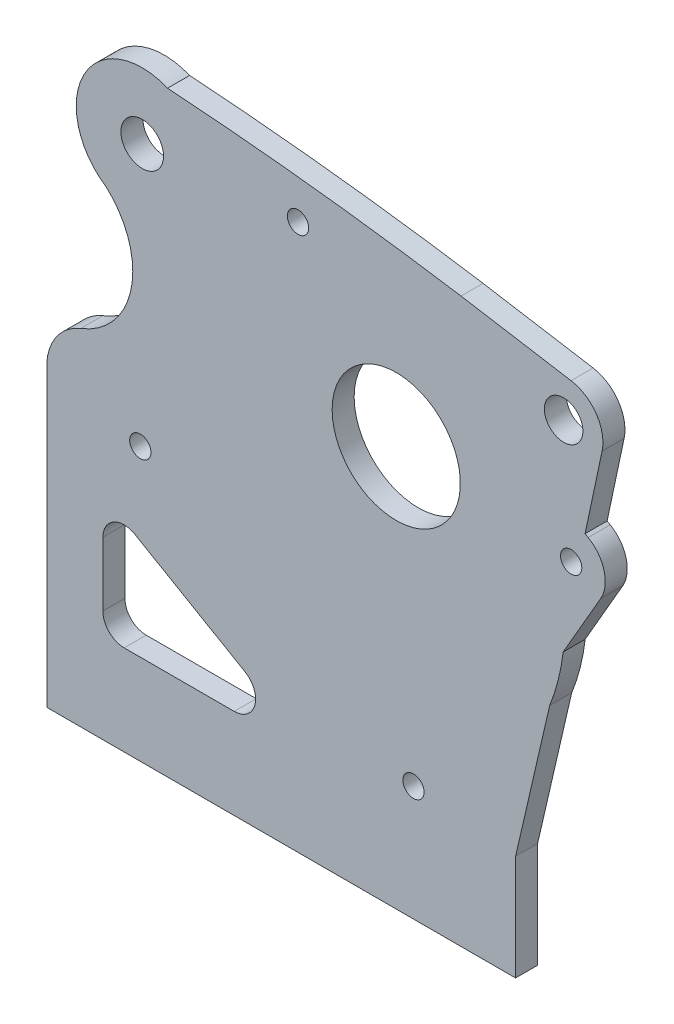
SolidWorks part; units mm, degrees
ref_plane "Front Plane" through (0, 0, 0) normal (0, 0, 1) x (1, 0, 0)
ref_plane "Top Plane" through (0, 0, 0) normal (0, 1, 0) x (1, 0, 0)
ref_plane "Right Plane" through (0, 0, 0) normal (1, 0, 0) x (0, 0, -1)
sketch "Sketch1" plane through (0, 0, 0) normal (0, 0, 1) x (1, 0, 0)
  line L0 (39.8842, 73.8588) -> (39.8845, 73.8606)
  line L1 (39.8845, 73.8606) -> (39.8842, 73.8588)
  line L2 (39.8842, 73.8588) -> (70.5949, 68.7626)
  line L3 (79.3303, 55.9518) -> (74.5417, 33.4234)
  line L4 (74.5417, 33.4234) -> (75.4194, 32.9167)
  line L5 (78.9332, 19.8029) -> (68.3677, 1.5028)
  line L6 (64.5642, -13.4817) -> (54.9782, -55.0033)
  line L7 (54.9782, -55.0033) -> (54.9678, -84.7033)
  line L8 (54.9678, -84.7033) -> (-77.0322, -84.7033)
  line L9 (-77.0322, -84.7033) -> (-77.0322, -52.3033)
  line L10 (-77.0322, -52.3033) -> (-77.0322, -0.7033)
  line L11 (39.6146, 73.9035) -> (39.8842, 73.8588)
  line L12 (-61.2322, -35.3033) -> (-61.2322, -53.3033)
  line L13 (-55.2322, -59.3033) -> (-24.2322, -59.3033)
  line L14 (-21.2193, -48.1145) -> (-52.2193, -30.1145)
  line L15 (39.8842, 73.8588) -> (39.8845, 73.8606)
  line L16 (39.8845, 73.8606) -> (39.8842, 73.8588)
  line L17 (39.8842, 73.8588) -> (70.5949, 68.7626)
  line L18 (79.3303, 55.9518) -> (74.5417, 33.4234)
  line L19 (74.5417, 33.4234) -> (75.4194, 32.9167)
  line L20 (78.9332, 19.8029) -> (68.3677, 1.5028)
  line L21 (64.5642, -13.4817) -> (54.9782, -55.0033)
  line L22 (54.9782, -55.0033) -> (54.9678, -84.7033)
  line L23 (54.9678, -84.7033) -> (-77.0322, -84.7033)
  line L24 (-77.0322, -84.7033) -> (-77.0322, -52.3033)
  line L25 (-77.0322, -52.3033) -> (-77.0322, -0.7033)
  line L26 (39.6146, 73.9035) -> (39.8842, 73.8588)
  line L27 (-61.2322, -35.3033) -> (-61.2322, -53.3033)
  line L28 (-55.2322, -59.3033) -> (-24.2322, -59.3033)
  line L29 (-21.2193, -48.1145) -> (-52.2193, -30.1145)
  circle A0 centre (68.505, 58.1264) radius 5.4293
  circle A1 centre (-50.1509, 66.1239) radius 6
  circle A2 centre (-50.1509, 66.1239) radius 3.5
  circle A3 centre (-6.2837, 69.0029) radius 3
  circle A4 centre (26.2194, -52.3002) radius 3
  circle A5 centre (70.6194, 24.6029) radius 3
  circle A6 centre (-50.6837, -7.9002) radius 3
  circle A7 centre (21.3678, 28.0967) radius 6.5
  circle A8 centre (21.3678, 28.0967) radius 18.05
  circle A9 centre (68.505, 58.1264) radius 5.4293
  circle A10 centre (-50.1509, 66.1239) radius 6
  circle A11 centre (-50.1509, 66.1239) radius 3.5
  circle A12 centre (-6.2837, 69.0029) radius 3
  circle A13 centre (26.2194, -52.3002) radius 3
  circle A14 centre (70.6194, 24.6029) radius 3
  circle A15 centre (-50.6837, -7.9002) radius 3
  circle A16 centre (21.3678, 28.0967) radius 6.5
  circle A17 centre (21.3678, 28.0967) radius 18.05
  arc A18 (79.3303, 55.9518) -> (70.5949, 68.7626) centre (68.8391, 58.1817) ccw
  arc A19 (78.9332, 19.8029) -> (75.4194, 32.9167) centre (70.6194, 24.6029) ccw
  arc A20 (64.5642, -13.4817) -> (68.3677, 1.5028) centre (9.9678, 8.3513) ccw
  arc A21 (-67.4322, 12.4967) -> (-77.0322, -0.7033) centre (-61.6525, -1.7976) ccw
  arc A22 (-67.4322, 12.4967) -> (-60.3544, 50.5971) centre (-75.5013, 33.7033) ccw
  arc A23 (-43.0154, 83.2784) -> (-60.3544, 50.5971) centre (-50.1509, 66.1239) ccw
  arc A24 (39.6146, 73.9035) -> (-43.0154, 83.2784) centre (-106.7923, -847.6817) ccw
  arc A25 (-52.2193, -30.1145) -> (-61.2322, -35.3033) centre (-55.2322, -35.3033) ccw
  arc A26 (-61.2322, -53.3033) -> (-55.2322, -59.3033) centre (-55.2322, -53.3033) ccw
  arc A27 (-24.2322, -59.3033) -> (-21.2193, -48.1145) centre (-24.2322, -53.3033) ccw
  arc A28 (79.3303, 55.9518) -> (70.5949, 68.7626) centre (68.8391, 58.1817) ccw
  arc A29 (78.9332, 19.8029) -> (75.4194, 32.9167) centre (70.6194, 24.6029) ccw
  arc A30 (64.5642, -13.4817) -> (68.3677, 1.5028) centre (9.9678, 8.3513) ccw
  arc A31 (-67.4322, 12.4967) -> (-77.0322, -0.7033) centre (-61.6525, -1.7976) ccw
  arc A32 (-67.4322, 12.4967) -> (-60.3544, 50.5971) centre (-75.5013, 33.7033) ccw
  arc A33 (-43.0154, 83.2784) -> (-60.3544, 50.5971) centre (-50.1509, 66.1239) ccw
  arc A34 (39.6146, 73.9035) -> (-43.0154, 83.2784) centre (-106.7923, -847.6817) ccw
  arc A35 (-52.2193, -30.1145) -> (-61.2322, -35.3033) centre (-55.2322, -35.3033) ccw
  arc A36 (-61.2322, -53.3033) -> (-55.2322, -59.3033) centre (-55.2322, -53.3033) ccw
  arc A37 (-24.2322, -59.3033) -> (-21.2193, -48.1145) centre (-24.2322, -53.3033) ccw
extrude "Boss-Extrude1" add sketch "Sketch1" along normal blind 6.2 contours L11 A24 A23 A22 A21 L10 L9 L8 L7 L6 A20 L5 A19 L4 L3 A18 L2 A27 L13 A26 L12 A25 L14 A0 A1 A3 A4 A5 A6 A8
